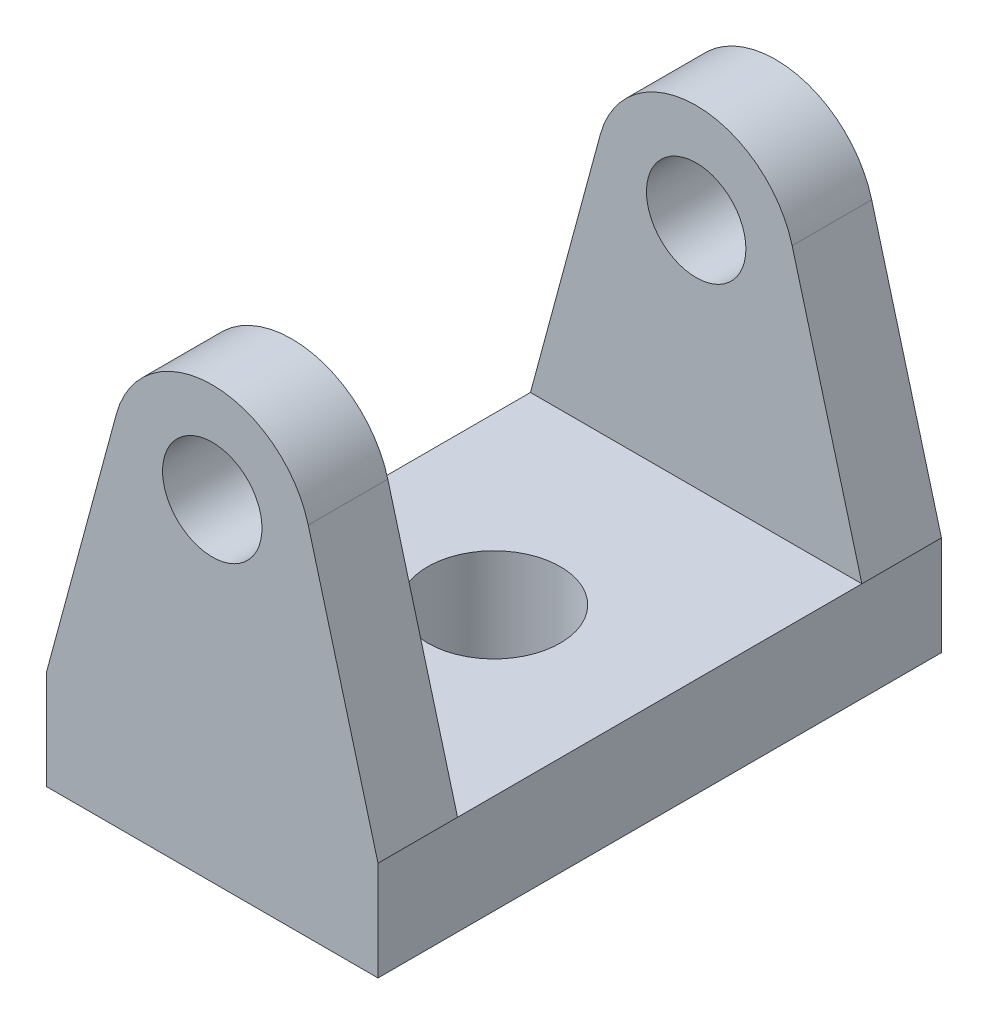
SolidWorks part; units mm, degrees
ref_plane "Front Plane" through (0, 0, 0) normal (0, 0, 1) x (1, 0, 0)
ref_plane "Top Plane" through (0, 0, 0) normal (0, 1, 0) x (1, 0, 0)
ref_plane "Right Plane" through (0, 0, 0) normal (1, 0, 0) x (0, 0, -1)
sketch "Sketch1" plane through (0, 0, 0) normal (0, 0, 1) x (1, 0, 0)
  line L0 (0, 0) -> (-59530.8761, 0) construction
  line L1 (0, 0) -> (0, 59530.8761) construction
  line L2 (0, 0) -> (0, 15)
  line L5 (50, 15) -> (50, 0)
  line L6 (50, 0) -> (0, 0)
  line L7 (0, 15) -> (10.5198, 53.9145)
  line L8 (50, 15) -> (39.4802, 53.9145)
  circle A0 centre (25, 50) radius 15
  circle A1 centre (25, 50) radius 7.5
  point P14 (25, 0)
  point P15 (0, 0)
  point P17 (36.152, 37.5986)
  dimension "D1" = 15
  dimension "D2" = 30
  dimension "D3" = 50
  dimension "D4" = 0
  dimension "D5" = 50
  dimension "D6" = 15
  dimension "D7" = 15
extrude "Boss-Extrude1" add sketch "Sketch1" against normal blind 85 contours A0 L7 L2 L6 L5 L8 | A0 A1
sketch "Sketch2" plane through (0, 0, 0) normal (1, 0, 0) x (0, 0, -1)
  line L0 (12, 65.9653) -> (12, 15)
  line L2 (85, 15) -> (0, 15) construction
  line L3 (12, 15) -> (73, 15)
  line L4 (73, 15) -> (73, 65.9653)
  line L5 (73, 65.9653) -> (12, 65.9653)
  line L6 (0, 15) -> (0, 53.9145) construction
  dimension "D1" = 61
  dimension "D2" = 12
extrude "Cut-Extrude1" cut sketch "Sketch2" along normal blind 71
sketch "Sketch3" plane through (0, 15, 0) normal (0, 1, 0) x (1, 0, 0)
  line L0 (10.5198, 73) -> (39.4802, 73) construction
  line L2 (50, 12) -> (50, 73) construction
  circle A0 centre (25, 42.5) radius 10
  point P4 (0, 0)
  point P6 (44.3161, 55.6562)
  dimension "D1" = 20
  dimension "D2" = 30.5
  dimension "D3" = 25
extrude "Cut-Extrude2" cut sketch "Sketch3" against normal blind 23
